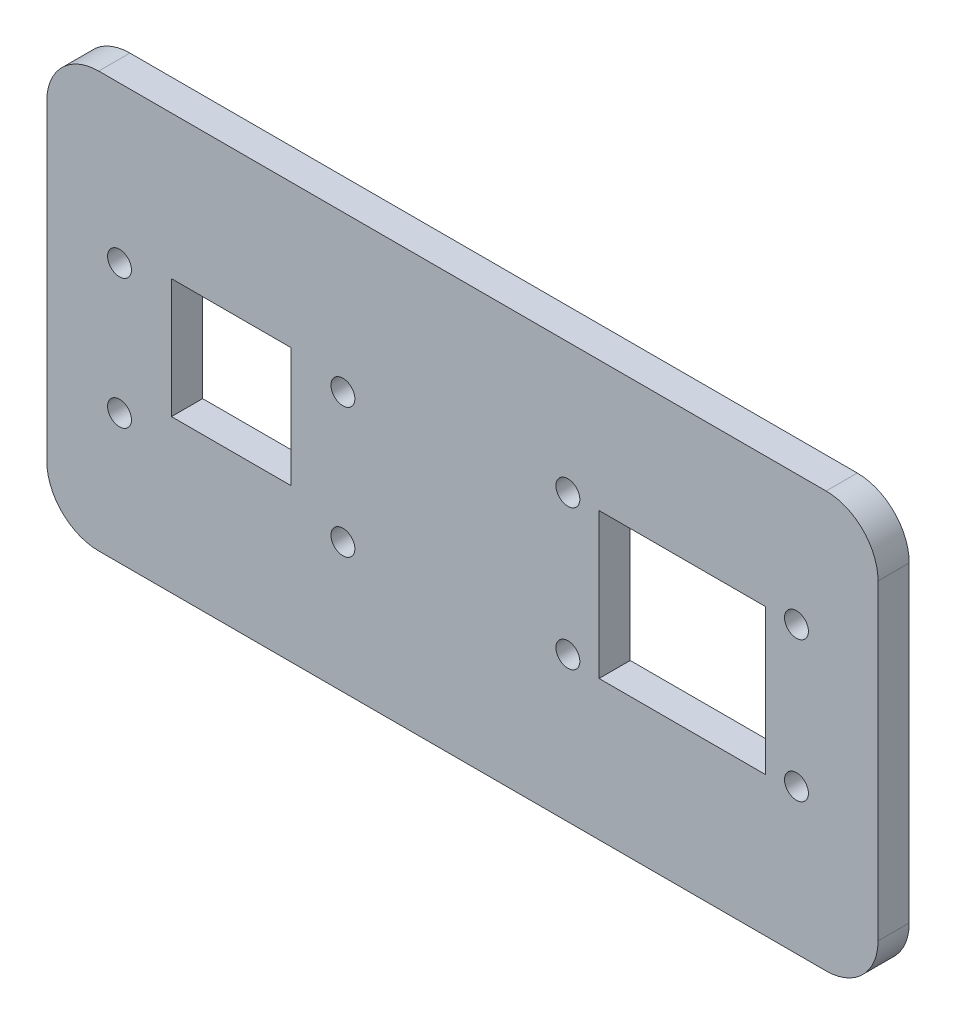
SolidWorks part; units mm, degrees
ref_plane "Front Plane" through (0, 0, 0) normal (0, 0, 1) x (1, 0, 0)
ref_plane "Top Plane" through (0, 0, 0) normal (0, 1, 0) x (1, 0, 0)
ref_plane "Right Plane" through (0, 0, 0) normal (1, 0, 0) x (0, 0, -1)
sketch "Sketch1" plane through (0, 0, 0) normal (0, 0, 1) x (1, 0, 0)
  line L1 (-40, 20) -> (40, 20)
  line L2 (-40, 20) -> (-40, -20)
  line L3 (-40, -20) -> (40, -20)
  line L4 (40, 20) -> (40, -20)
  line L5 (-40, 20) -> (40, -20) construction
  line L6 (-40, -20) -> (40, 20) construction
  line L7 (-28, 6.2) -> (-16.5, 6.2)
  line L8 (-28, 6.2) -> (-28, -5.3)
  line L9 (-28, -5.3) -> (-16.5, -5.3)
  line L10 (-16.5, 6.2) -> (-16.5, -5.3)
  line L11 (-28, 6.2) -> (-16.5, -5.3) construction
  line L12 (-28, -5.3) -> (-16.5, 6.2) construction
  line L13 (13.15, 7.45) -> (29.15, 7.45)
  line L14 (13.15, 7.45) -> (13.15, -6.55)
  line L15 (13.15, -6.55) -> (29.15, -6.55)
  line L16 (29.15, 7.45) -> (29.15, -6.55)
  line L17 (13.15, 7.45) -> (29.15, -6.55) construction
  line L18 (13.15, -6.55) -> (29.15, 7.45) construction
  circle A0 centre (-11.5, 5) radius 1.15
  circle A1 centre (-11.5, -7.5) radius 1.15
  circle A2 centre (-33, 5) radius 1.15
  circle A3 centre (-33, -7.5) radius 1.15
  circle A4 centre (10.15, 7.45) radius 1.15
  circle A5 centre (10.15, -6.05) radius 1.15
  circle A6 centre (32.15, 7.45) radius 1.15
  circle A7 centre (32.15, -6.05) radius 1.15
  point P0 (0, 0)
  point P6 (-22.25, 0.45)
  point P11 (21.15, 0.45)
  dimension "D1" = 2.3
  dimension "D2" = 2.3
  dimension "D3" = 2.3
  dimension "D4" = 2.3
  dimension "D6" = 5
  dimension "D7" = 1.2
  dimension "D11" = 2.3
  dimension "D13" = 3
  dimension "D14" = 13.5
  dimension "D15" = 21.65
  dimension "D17" = 7
  dimension "D19" = 15
  dimension "D5" = 12.5
  dimension "D8" = 5
  dimension "D9" = 11.5
  dimension "D10" = 11.5
  dimension "D12" = 3
  dimension "D16" = 80
  dimension "D18" = 40
  dimension "D20" = 16
  dimension "D21" = 14
extrude "Boss-Extrude1" add sketch "Sketch1" along normal blind 3
fillet "Fillet1" radius 5 4 edges at (40, 20, 1.5) (40, -20, 1.5) (-40, -20, 1.5) (-40, 20, 1.5)
